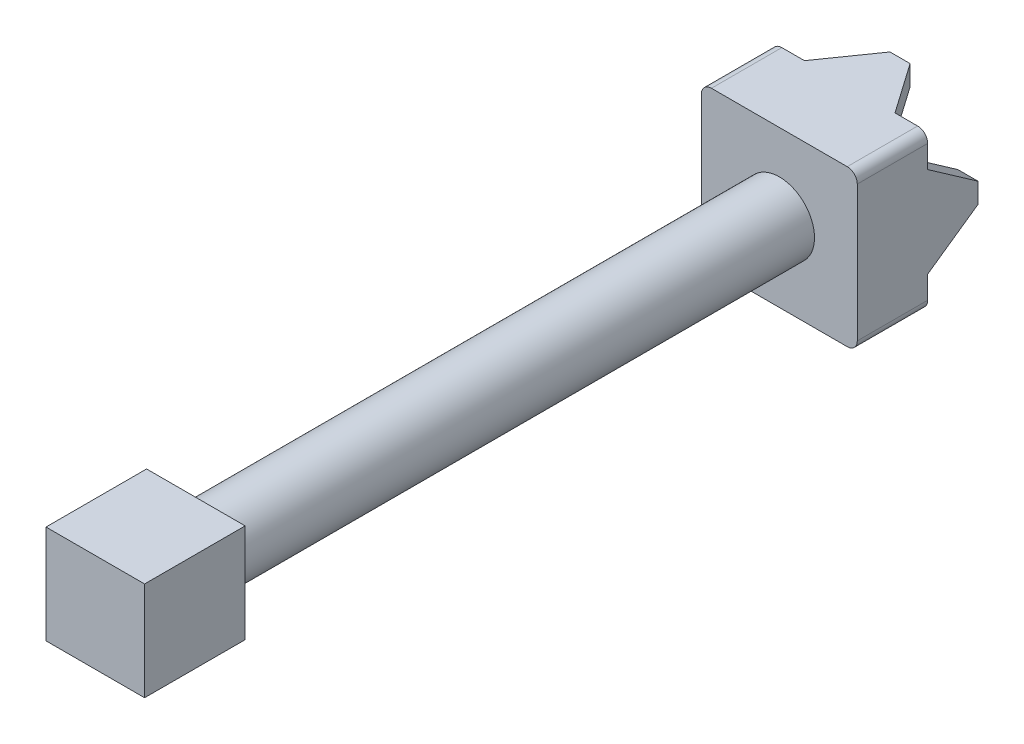
SolidWorks part; units mm, degrees
ref_plane "Front" through (0, 0, 0) normal (0, 0, 1) x (1, 0, 0)
ref_plane "Top" through (0, 0, 0) normal (0, 1, 0) x (1, 0, 0)
ref_plane "Right" through (0, 0, 0) normal (1, 0, 0) x (0, 0, -1)
sketch "草图1" plane through (0, 0, 0) normal (0, 0, 1) x (1, 0, 0)
  line L0 (-27.0338, 10.0673) -> (-17.5338, 10.0673)
  line L1 (-30.0338, 13.0673) -> (-14.5338, 13.0673)
  line L2 (-30.0338, 10.0673) -> (-30.0338, -2.4327)
  line L3 (-30.0338, -2.4327) -> (-14.5338, -2.4327)
  line L4 (-14.5338, 13.0673) -> (-14.5338, -2.4327)
  line L6 (-30.0338, 13.0673) -> (-30.0338, 10.0673)
  line L13 (-17.5338, 0.5673) -> (-17.5338, 10.0673)
  line L14 (-27.0338, 10.0673) -> (-27.0338, 0.5673)
  line L15 (-17.5338, 0.5673) -> (-27.0338, 0.5673)
  dimension "D1" = 15.5
  dimension "D2" = 15.5
  dimension "D4" = 3
extrude "凸台-拉伸2" add sketch "草图1" along normal blind 5
fillet "圆角2" radius 1 4 edges at (-30.0338, -2.4327, 2.5) (-30.0338, 13.0673, 2.5) (-14.5338, -2.4327, 2.5) (-14.5338, 13.0673, 2.5)
sketch "草图2" plane through (0, 0, 5) normal (0, 0, 1) x (1, 0, 0)
  line L0 (-27.0338, 10.0673) -> (-17.5338, 10.0673)
  line L1 (-22.2838, 10.0673) -> (-22.2838, 0.5673)
  line L2 (-27.0338, 0.5673) -> (-17.5338, 0.5673) construction
  circle A0 centre (-22.2838, 5.3173) radius 5.5
  line M10 (-17.5338, 0.5673) -> (-27.0338, 0.5673)
  line M11 (-27.0338, 0.5673) -> (-27.0338, 10.0673)
  line M13 (-17.5338, 10.0673) -> (-17.5338, 0.5673)
  dimension "D2" = 11
  dimension "D1" = 9.5
extrude "切除-拉伸1" cut sketch "草图2" against normal through all contours A0 M13 | L0 A0 | A0 M11 | A0 M10
sketch "草图4" plane through (0, 0, 5) normal (0, 0, 1) x (1, 0, 0)
  line L1 (-27.0338, 10.0673) -> (-17.5338, 10.0673)
  line L2 (-27.0338, 10.0673) -> (-27.0338, 0.5673)
  line L3 (-27.0338, 0.5673) -> (-17.5338, 0.5673)
  line L4 (-17.5338, 10.0673) -> (-17.5338, 0.5673)
  circle A0 centre (-22.2838, 5.3173) radius 5.5
  line M2 (-19.5111, 10.0673) -> (-17.5338, 10.0673)
  line M3 (-17.5338, 10.0673) -> (-17.5338, 8.09)
  line M5 (-17.5338, 2.5447) -> (-17.5338, 0.5673)
  line M6 (-17.5338, 0.5673) -> (-19.5111, 0.5673)
  line M8 (-25.0564, 0.5673) -> (-27.0338, 0.5673)
  line M9 (-27.0338, 0.5673) -> (-27.0338, 2.5447)
  line M11 (-27.0338, 8.09) -> (-27.0338, 10.0673)
  line M12 (-27.0338, 10.0673) -> (-25.0564, 10.0673)
extrude "凸台-拉伸3" add sketch "草图4" against normal blind 5 contours A0 M12 M11 | A0 M3 M2 | A0 M6 M5 | A0 M9 M8
sketch "草图6" plane through (0, 0, 5) normal (0, 0, 1) x (1, 0, 0)
  line L0 (-30.0338, 5.3173) -> (-14.5338, 5.3173)
  line L1 (-30.0338, 12.0673) -> (-30.0338, -1.4327) construction
  line L2 (-14.5338, -1.4327) -> (-14.5338, 12.0673) construction
ref_plane "基准面1" through (0, 5.3173, 0) normal (0, -1, 0) x (1, 0, 0)
sketch "草图7" plane through (0, 5.3173, 0) normal (0, -1, 0) x (1, 0, 0)
  line L0 (-22.2838, 5) -> (-14.5338, 5)
  line L1 (-30.0338, 5) -> (-14.5338, 5) construction
  line L2 (-22.2838, 5) -> (-22.2838, 8)
  line L3 (-22.2838, 8) -> (-17.2838, 8)
  line L4 (-17.2838, 8) -> (-14.5338, 5)
  dimension "D1" = 3
  dimension "D2" = 5
sketch "草图9" plane through (0, -2.4327, 0) normal (0, -1, 0) x (1, 0, 0)
  line L0 (-22.2838, 0) -> (-26.7838, 0)
  line L1 (-29.0338, 0) -> (-15.5338, 0) construction
  line L2 (-22.2838, 0) -> (-17.7838, 0)
  line L3 (-22.2838, 0) -> (-22.2838, -5)
  line L4 (-22.2838, -5) -> (-23.2838, -5)
  line L5 (-22.2838, -5) -> (-21.2838, -5)
  line L6 (-26.7838, 0) -> (-23.2838, -5)
  line L7 (-21.2838, -5) -> (-17.7838, 0)
  line M8 (-29.0338, 0) -> (-15.5338, 0)
  dimension "D1" = 4.5
  dimension "D2" = 4.5
  dimension "D3" = 5
  dimension "D4" = 1
  dimension "D5" = 1
extrude "凸台-拉伸5" add sketch "草图9" against normal blind 2 contours L6 L4 L3 M8 | L5 L7 L3 M8
sketch "草图10" plane through (-14.5338, 0, 0) normal (1, 0, 0) x (0, 0, -1)
  line L0 (0, 5.3173) -> (0, 0.8173)
  line L1 (0, -1.4327) -> (0, 12.0673) construction
  line L2 (0, 5.3173) -> (0, 9.8173)
  line L3 (0, 5.3173) -> (5, 5.3173)
  line L4 (5, 5.3173) -> (5, 4.3173)
  line L5 (5, 5.3173) -> (5, 6.3173)
  line L6 (5, 4.3173) -> (0, 0.8173)
  line L7 (5, 6.3173) -> (0, 9.8173)
  line M8 (0, -1.4327) -> (0, 12.0673)
  dimension "D1" = 4.5
  dimension "D2" = 4.5
  dimension "D3" = 5
  dimension "D4" = 1
  dimension "D5" = 1
extrude "凸台-拉伸6" add sketch "草图10" against normal blind 2 contours L6 L4 L3 M8 | L5 L7 L3 M8
sketch "草图11" plane through (-30.0338, 0, 0) normal (-1, 0, 0) x (0, 0, 1)
  line L0 (0, 5.3173) -> (0, 9.8173)
  line L1 (0, 12.0673) -> (0, -1.4327) construction
  line L2 (0, 5.3173) -> (0, 0.8173)
  line L3 (0, 5.3173) -> (-5, 5.3173)
  line L4 (-5, 5.3173) -> (-5, 4.3173)
  line L5 (-5, 5.3173) -> (-5, 6.3173)
  line L6 (-5, 4.3173) -> (0, 0.8173)
  line L7 (-5, 6.3173) -> (0, 9.8173)
  line M6 (0, 12.0673) -> (0, -1.4327)
  dimension "D1" = 4.5
  dimension "D2" = 4.5
  dimension "D3" = 5
  dimension "D4" = 1
  dimension "D5" = 1
extrude "凸台-拉伸7" add sketch "草图11" against normal blind 2 contours L4 L6 L3 M6 | L7 L5 L3 M6
sketch "草图12" plane through (0, 13.0673, 0) normal (0, 1, 0) x (1, 0, 0)
  line L0 (-22.2838, 0) -> (-17.7838, 0)
  line L1 (-15.5338, 0) -> (-29.0338, 0) construction
  line L2 (-22.2838, 0) -> (-26.7838, 0)
  line L3 (-22.2838, 0) -> (-22.2838, 5)
  line L4 (-22.2838, 5) -> (-21.2838, 5)
  line L5 (-22.2838, 5) -> (-23.2838, 5)
  line L6 (-23.2838, 5) -> (-26.7838, 0)
  line L7 (-21.2838, 5) -> (-17.7838, 0)
  point P4 (-21.7838, 5)
  line M5 (-15.5338, 0) -> (-29.0338, 0)
  dimension "D1" = 5
  dimension "D2" = 1
  dimension "D3" = 1
  dimension "D4" = 4.5
  dimension "D5" = 4.5
extrude "凸台-拉伸8" add sketch "草图12" against normal blind 2 contours L5 L6 L3 M5 | L7 L4 L3 M5
sketch "草图13" plane through (0, 0, 5) normal (0, 0, 1) x (1, 0, 0)
  line L0 (-30.0338, 5.3173) -> (-14.5338, 5.3173) construction
  line L5 (-30.0338, 12.0673) -> (-30.0338, -1.4327)
  line L6 (-29.0338, -2.4327) -> (-15.5338, -2.4327)
  line L7 (-14.5338, -1.4327) -> (-14.5338, 12.0673)
  line L8 (-15.5338, 13.0673) -> (-29.0338, 13.0673)
  line L9 (-30.0338, 12.0673) -> (-30.0338, -1.4327)
  line L10 (-29.0338, -2.4327) -> (-15.5338, -2.4327)
  line L11 (-14.5338, -1.4327) -> (-14.5338, 12.0673)
  line L12 (-15.5338, 13.0673) -> (-29.0338, 13.0673)
  arc A5 (-30.0338, -1.4327) -> (-29.0338, -2.4327) centre (-29.0338, -1.4327) ccw
  arc A6 (-15.5338, -2.4327) -> (-14.5338, -1.4327) centre (-15.5338, -1.4327) ccw
  arc A7 (-14.5338, 12.0673) -> (-15.5338, 13.0673) centre (-15.5338, 12.0673) ccw
  arc A8 (-29.0338, 13.0673) -> (-30.0338, 12.0673) centre (-29.0338, 12.0673) ccw
  arc A9 (-30.0338, -1.4327) -> (-29.0338, -2.4327) centre (-29.0338, -1.4327) ccw
  arc A10 (-15.5338, -2.4327) -> (-14.5338, -1.4327) centre (-15.5338, -1.4327) ccw
  arc A11 (-14.5338, 12.0673) -> (-15.5338, 13.0673) centre (-15.5338, 12.0673) ccw
  arc A12 (-29.0338, 13.0673) -> (-30.0338, 12.0673) centre (-29.0338, 12.0673) ccw
  point P0 (-22.2838, 5.3173)
  dimension "D1" = 0
extrude "凸台-拉伸10" add sketch "草图13" along normal blind 2
sketch "草图15" plane through (0, 0, 7) normal (0, 0, 1) x (1, 0, 0)
  line L0 (-30.0338, 5.3173) -> (-14.5338, 5.3173) construction
  circle A0 centre (-22.2838, 5.3173) radius 3.5
  dimension "D1" = 7
extrude "凸台-拉伸11" add sketch "草图15" along normal blind 58
sketch "草图16" plane through (0, 0, 65) normal (0, 0, 1) x (1, 0, 0)
  line L1 (-27.1838, 10.2173) -> (-17.3838, 10.2173)
  line L2 (-27.1838, 10.2173) -> (-27.1838, 0.4173)
  line L3 (-27.1838, 0.4173) -> (-17.3838, 0.4173)
  line L4 (-17.3838, 10.2173) -> (-17.3838, 0.4173)
  line L5 (-27.1838, 10.2173) -> (-17.3838, 0.4173) construction
  line L6 (-27.1838, 0.4173) -> (-17.3838, 10.2173) construction
  point P0 (-22.2838, 5.3173)
  dimension "D1" = 9.8
  dimension "D2" = 9.8
extrude "凸台-拉伸12" add sketch "草图16" along normal blind 10
